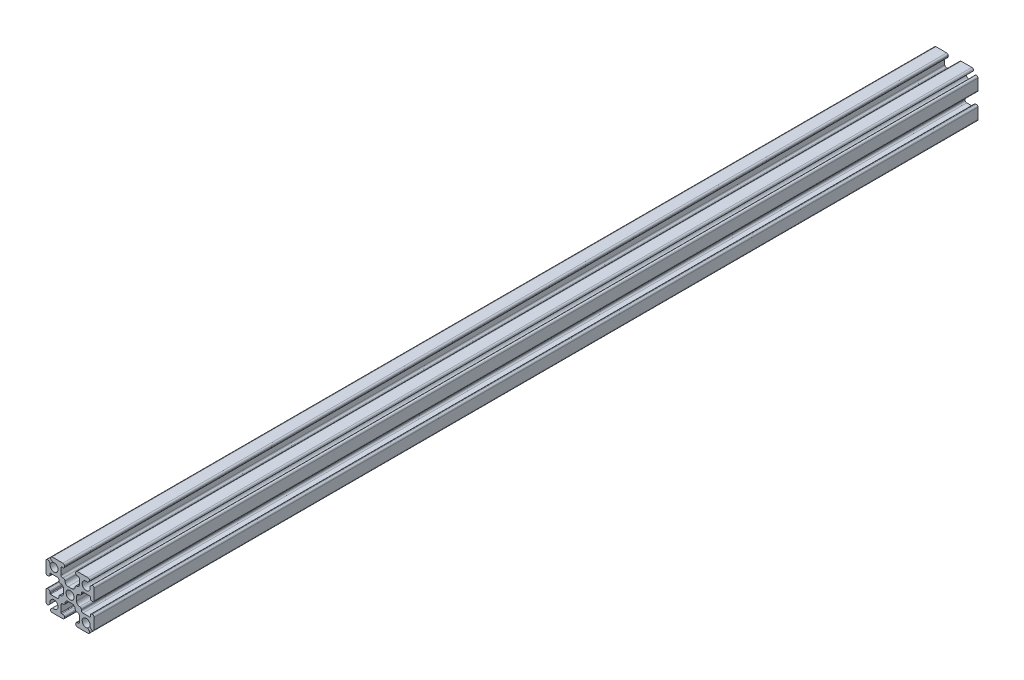
SolidWorks part; units mm, degrees
ref_plane "Front" through (0, 0, 0) normal (0, 0, 1) x (1, 0, 0)
ref_plane "Top" through (0, 0, 0) normal (0, 1, 0) x (1, 0, 0)
ref_plane "Right" through (0, 0, 0) normal (1, 0, 0) x (0, 0, -1)
sketch "Sketch1" plane through (0, 0, 0) normal (0, 0, 1) x (1, 0, 0)
  line L0 (6.6464, 5.9393) -> (6.1636, 5.4565)
  line L1 (5.4565, 6.1636) -> (5.9393, 6.6464)
  line L2 (5.5858, 7.5) -> (2.25, 7.5)
  line L3 (1.75, 7) -> (1.75, 6.8)
  line L4 (2.25, 6.3) -> (2.65, 6.3)
  line L5 (2.85, 6.1) -> (2.85, 4)
  line L6 (2.35, 3.5) -> (2.1, 3.5)
  line L7 (0.6, 2) -> (-0.6, 2)
  line L8 (-2.1, 3.5) -> (-2.35, 3.5)
  line L9 (-2.85, 4) -> (-2.85, 6.1)
  line L10 (-2.65, 6.3) -> (-2.25, 6.3)
  line L11 (-1.75, 6.8) -> (-1.75, 7)
  line L12 (-2.25, 7.5) -> (-5.5858, 7.5)
  line L13 (-5.9393, 6.6464) -> (-5.4565, 6.1636)
  line L14 (-6.1636, 5.4565) -> (-6.6464, 5.9393)
  line L15 (-7.5, 5.5858) -> (-7.5, 2.25)
  line L16 (-7, 1.75) -> (-6.8, 1.75)
  line L17 (-6.3, 2.25) -> (-6.3, 2.65)
  line L18 (-6.1, 2.85) -> (-4, 2.85)
  line L19 (-3.5, 2.35) -> (-3.5, 2.1)
  line L20 (-2, 0.6) -> (-2, -0.6)
  line L21 (-3.5, -2.1) -> (-3.5, -2.35)
  line L22 (-4, -2.85) -> (-6.1, -2.85)
  line L23 (-6.3, -2.65) -> (-6.3, -2.25)
  line L24 (-6.8, -1.75) -> (-7, -1.75)
  line L25 (-7.5, -2.25) -> (-7.5, -5.5858)
  line L26 (-6.6464, -5.9393) -> (-6.1636, -5.4565)
  line L27 (-5.4565, -6.1636) -> (-5.9393, -6.6464)
  line L28 (-5.5858, -7.5) -> (-2.25, -7.5)
  line L29 (-1.75, -7) -> (-1.75, -6.8)
  line L30 (-2.25, -6.3) -> (-2.65, -6.3)
  line L31 (-2.85, -6.1) -> (-2.85, -4)
  line L32 (-2.35, -3.5) -> (-2.1, -3.5)
  line L33 (-0.6, -2) -> (0.6, -2)
  line L34 (2.1, -3.5) -> (2.35, -3.5)
  line L35 (2.85, -4) -> (2.85, -6.1)
  line L36 (2.65, -6.3) -> (2.25, -6.3)
  line L37 (1.75, -6.8) -> (1.75, -7)
  line L38 (2.25, -7.5) -> (5.5858, -7.5)
  line L39 (5.9393, -6.6464) -> (5.4565, -6.1636)
  line L40 (6.1636, -5.4565) -> (6.6464, -5.9393)
  line L41 (7.5, -5.5858) -> (7.5, -2.25)
  line L42 (7, -1.75) -> (6.8, -1.75)
  line L43 (6.3, -2.25) -> (6.3, -2.65)
  line L44 (6.1, -2.85) -> (4, -2.85)
  line L45 (3.5, -2.35) -> (3.5, -2.1)
  line L46 (2, -0.6) -> (2, 0.6)
  line L47 (3.5, 2.1) -> (3.5, 2.35)
  line L48 (4, 2.85) -> (6.1, 2.85)
  line L49 (6.3, 2.65) -> (6.3, 2.25)
  line L50 (6.8, 1.75) -> (7, 1.75)
  line L51 (7.5, 2.25) -> (7.5, 5.5858)
  circle A0 centre (0, 0) radius 1.25
  arc A1 (6.1636, 5.4565) -> (5.4565, 6.1636) centre (5, 5) cw
  arc A2 (5.9393, 6.6464) -> (5.5858, 7.5) centre (5.5858, 7) ccw
  arc A3 (2.25, 7.5) -> (1.75, 7) centre (2.25, 7) ccw
  arc A4 (1.75, 6.8) -> (2.25, 6.3) centre (2.25, 6.8) ccw
  arc A5 (2.65, 6.3) -> (2.85, 6.1) centre (2.65, 6.1) cw
  arc A6 (2.85, 4) -> (2.35, 3.5) centre (2.35, 4) cw
  arc A7 (2.1, 3.5) -> (1.6, 3) centre (2.1, 3) ccw
  arc A8 (1.6, 3) -> (0.6, 2) centre (0.6, 3) cw
  arc A9 (-0.6, 2) -> (-1.6, 3) centre (-0.6, 3) cw
  arc A10 (-1.6, 3) -> (-2.1, 3.5) centre (-2.1, 3) ccw
  arc A11 (-2.35, 3.5) -> (-2.85, 4) centre (-2.35, 4) cw
  arc A12 (-2.85, 6.1) -> (-2.65, 6.3) centre (-2.65, 6.1) cw
  arc A13 (-2.25, 6.3) -> (-1.75, 6.8) centre (-2.25, 6.8) ccw
  arc A14 (-1.75, 7) -> (-2.25, 7.5) centre (-2.25, 7) ccw
  arc A15 (-5.5858, 7.5) -> (-5.9393, 6.6464) centre (-5.5858, 7) ccw
  arc A16 (-5.4565, 6.1636) -> (-6.1636, 5.4565) centre (-5, 5) cw
  arc A17 (-6.6464, 5.9393) -> (-7.5, 5.5858) centre (-7, 5.5858) ccw
  arc A18 (-7.5, 2.25) -> (-7, 1.75) centre (-7, 2.25) ccw
  arc A19 (-6.8, 1.75) -> (-6.3, 2.25) centre (-6.8, 2.25) ccw
  arc A20 (-6.3, 2.65) -> (-6.1, 2.85) centre (-6.1, 2.65) cw
  arc A21 (-4, 2.85) -> (-3.5, 2.35) centre (-4, 2.35) cw
  arc A22 (-3.5, 2.1) -> (-3, 1.6) centre (-3, 2.1) ccw
  arc A23 (-3, 1.6) -> (-2, 0.6) centre (-3, 0.6) cw
  arc A24 (-2, -0.6) -> (-3, -1.6) centre (-3, -0.6) cw
  arc A25 (-3, -1.6) -> (-3.5, -2.1) centre (-3, -2.1) ccw
  arc A26 (-3.5, -2.35) -> (-4, -2.85) centre (-4, -2.35) cw
  arc A27 (-6.1, -2.85) -> (-6.3, -2.65) centre (-6.1, -2.65) cw
  arc A28 (-6.3, -2.25) -> (-6.8, -1.75) centre (-6.8, -2.25) ccw
  arc A29 (-7, -1.75) -> (-7.5, -2.25) centre (-7, -2.25) ccw
  arc A30 (-7.5, -5.5858) -> (-6.6464, -5.9393) centre (-7, -5.5858) ccw
  arc A31 (-6.1636, -5.4565) -> (-5.4565, -6.1636) centre (-5, -5) cw
  arc A32 (-5.9393, -6.6464) -> (-5.5858, -7.5) centre (-5.5858, -7) ccw
  arc A33 (-2.25, -7.5) -> (-1.75, -7) centre (-2.25, -7) ccw
  arc A34 (-1.75, -6.8) -> (-2.25, -6.3) centre (-2.25, -6.8) ccw
  arc A35 (-2.65, -6.3) -> (-2.85, -6.1) centre (-2.65, -6.1) cw
  arc A36 (-2.85, -4) -> (-2.35, -3.5) centre (-2.35, -4) cw
  arc A37 (-2.1, -3.5) -> (-1.6, -3) centre (-2.1, -3) ccw
  arc A38 (-1.6, -3) -> (-0.6, -2) centre (-0.6, -3) cw
  arc A39 (0.6, -2) -> (1.6, -3) centre (0.6, -3) cw
  arc A40 (1.6, -3) -> (2.1, -3.5) centre (2.1, -3) ccw
  arc A41 (2.35, -3.5) -> (2.85, -4) centre (2.35, -4) cw
  arc A42 (2.85, -6.1) -> (2.65, -6.3) centre (2.65, -6.1) cw
  arc A43 (2.25, -6.3) -> (1.75, -6.8) centre (2.25, -6.8) ccw
  arc A44 (1.75, -7) -> (2.25, -7.5) centre (2.25, -7) ccw
  arc A45 (5.5858, -7.5) -> (5.9393, -6.6464) centre (5.5858, -7) ccw
  arc A46 (5.4565, -6.1636) -> (6.1636, -5.4565) centre (5, -5) cw
  arc A47 (6.6464, -5.9393) -> (7.5, -5.5858) centre (7, -5.5858) ccw
  arc A48 (7.5, -2.25) -> (7, -1.75) centre (7, -2.25) ccw
  arc A49 (6.8, -1.75) -> (6.3, -2.25) centre (6.8, -2.25) ccw
  arc A50 (6.3, -2.65) -> (6.1, -2.85) centre (6.1, -2.65) cw
  arc A51 (4, -2.85) -> (3.5, -2.35) centre (4, -2.35) cw
  arc A52 (3.5, -2.1) -> (3, -1.6) centre (3, -2.1) ccw
  arc A53 (3, -1.6) -> (2, -0.6) centre (3, -0.6) cw
  arc A54 (2, 0.6) -> (3, 1.6) centre (3, 0.6) cw
  arc A55 (3, 1.6) -> (3.5, 2.1) centre (3, 2.1) ccw
  arc A56 (3.5, 2.35) -> (4, 2.85) centre (4, 2.35) cw
  arc A57 (6.1, 2.85) -> (6.3, 2.65) centre (6.1, 2.65) cw
  arc A58 (6.3, 2.25) -> (6.8, 1.75) centre (6.8, 2.25) ccw
  arc A59 (7, 1.75) -> (7.5, 2.25) centre (7, 2.25) ccw
  arc A60 (7.5, 5.5858) -> (6.6464, 5.9393) centre (7, 5.5858) ccw
extrude "Boss-Extrude1" add sketch "Sketch1" along normal blind 424.19
sketch "Sketch2" plane through (0, 0, 0) normal (0, 0, -1) x (-1, 0, 0)
  line L1 (8.1576, 20.8097) -> (-10.9704, 20.8097)
  line L2 (8.1576, 20.8097) -> (8.1576, -15.0781)
  line L3 (8.1576, -15.0781) -> (-10.9704, -15.0781)
  line L4 (-10.9704, 20.8097) -> (-10.9704, -15.0781)
extrude "Cut-Extrude1" cut sketch "Sketch2" against normal blind 147.32
sketch "Sketch3" plane through (0, 0, 147.32) normal (0, 0, -1) x (-1, 0, 0)
  line L1 (27.7362, 36.8258) -> (-27.3073, 36.8258)
  line L2 (27.7362, 36.8258) -> (27.7362, -29.4825)
  line L3 (27.7362, -29.4825) -> (-27.3073, -29.4825)
  line L4 (-27.3073, 36.8258) -> (-27.3073, -29.4825)
extrude "Cut-Extrude2" cut sketch "Sketch3" against normal blind 1.77
